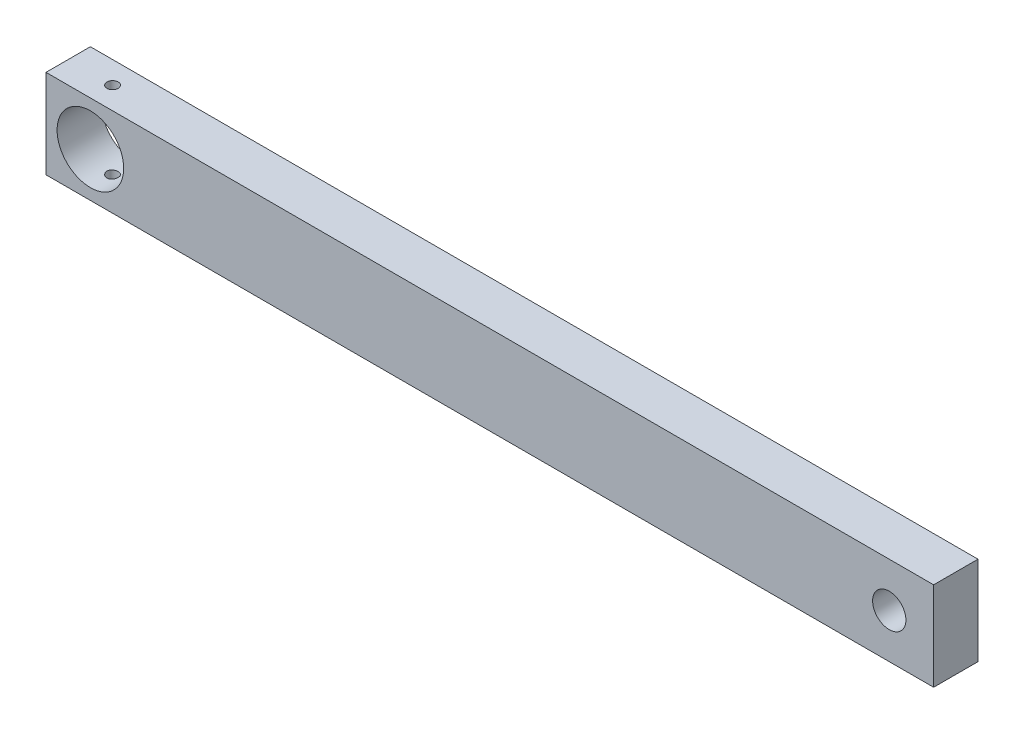
SolidWorks part; units mm, degrees
ref_plane "Front Plane" through (0, 0, 0) normal (0, 0, 1) x (1, 0, 0)
ref_plane "Top Plane" through (0, 0, 0) normal (0, 1, 0) x (1, 0, 0)
ref_plane "Right Plane" through (0, 0, 0) normal (1, 0, 0) x (0, 0, -1)
sketch "Sketch1" plane through (0, 0, 0) normal (0, 0, 1) x (1, 0, 0)
  line L1 (0, 0) -> (127, 0)
  line L2 (0, 0) -> (0, 12.7)
  line L3 (0, 12.7) -> (127, 12.7)
  line L4 (127, 0) -> (127, 12.7)
  circle A2 centre (6.35, 6.35) radius 4.7625
  circle A3 centre (120.65, 6.35) radius 2.3813
  dimension "D9" = 4.7625
  dimension "D10" = 6.35
  dimension "D11" = 6.35
  dimension "D12" = 9.525
  dimension "D13" = 6.35
  dimension "D14" = 6.35
  dimension "D1" = 12.7
  dimension "D2" = 127
other "AlignGroup1"
extrude "Boss-Extrude1" add sketch "Sketch1" along normal blind 6.35
sketch "Sketch2" plane through (0, 12.7, 0) normal (0, 1, 0) x (1, 0, 0)
  line L0 (0, -6.35) -> (0, 0) construction
  line L1 (127, -6.35) -> (0, -6.35) construction
  circle A0 centre (6.35, -3.175) radius 0.8001
  dimension "D1" = 1.6002
  dimension "D2" = 6.35
  dimension "D3" = 3.175
extrude "Cut-Extrude1" cut sketch "Sketch2" against normal blind 12.7
